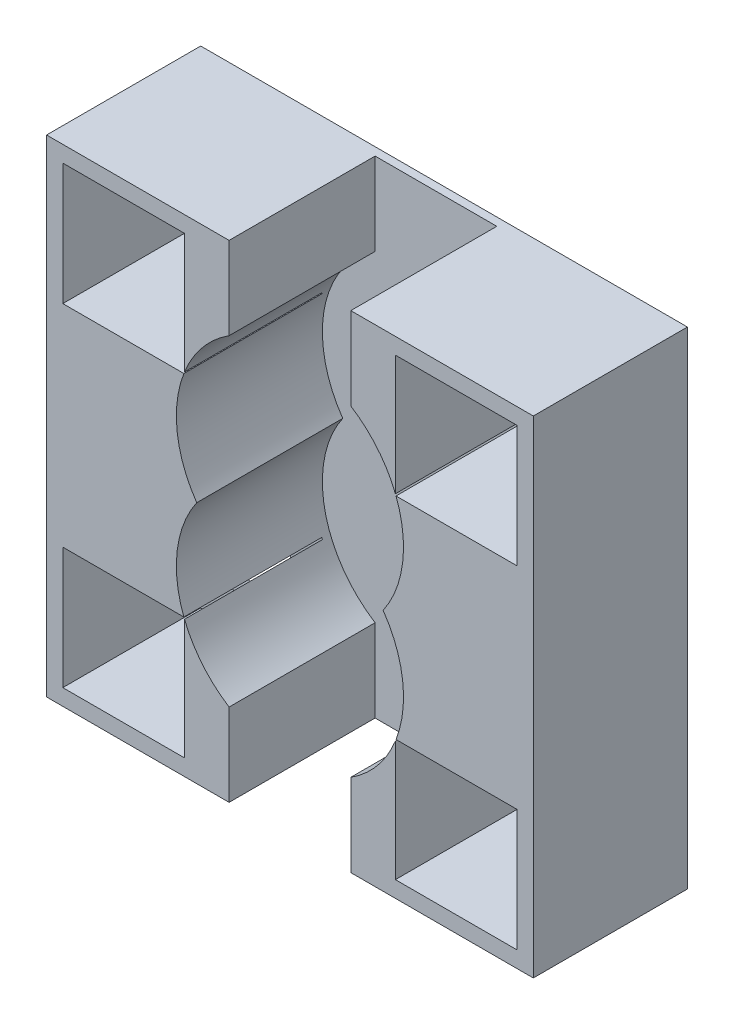
SolidWorks part; units mm, degrees
ref_plane "Plano frontal" through (0, 0, 0) normal (0, 0, 1) x (1, 0, 0)
ref_plane "Plano superior" through (0, 0, 0) normal (0, 1, 0) x (1, 0, 0)
ref_plane "Plano direito" through (0, 0, 0) normal (1, 0, 0) x (0, 0, -1)
sketch "Esboço1" plane through (0, 0, 0) normal (0, 0, 1) x (1, 0, 0)
  line L44 (-0.1299, 58.4128) -> (59.8701, 58.4128)
  line L45 (-0.1299, 58.4128) -> (-0.1299, -1.5872)
  line L46 (-0.1299, -1.5872) -> (59.8701, -1.5872)
  line L51 (59.8701, 58.4128) -> (59.8701, -1.5872)
  dimension "D1" = 60
  dimension "D2" = 60
extrude "Ressalto-extrusão2" add sketch "Esboço1" along normal blind 1 contours L45 L44 L51 L46
sketch "Esboço10" plane through (0, 0, 0) normal (0, 0, 1) x (1, 0, 0)
  line L9 (-0.1299, 58.4128) -> (59.8701, 58.4128)
  line L10 (-0.1299, 58.4128) -> (-0.1299, -1.5872)
  line L11 (-0.1299, -1.5872) -> (59.8701, -1.5872)
  line L12 (59.8701, 58.4128) -> (59.8701, -1.5872)
  arc A1 (18.381, 28.4128) -> (41.3593, 28.4128) centre (29.8701, 20.4128) ccw
  arc A2 (41.3593, 28.4128) -> (18.381, 28.4128) centre (29.8701, 36.4128) ccw
  dimension "D2" = 28
  dimension "D4" = 28
extrude "Ressalto-extrusão5" add sketch "Esboço10" along normal blind 19
sketch "Esboço13" plane through (0, 0, 19) normal (0, 0, 1) x (1, 0, 0)
  line L0 (59.8701, 58.4128) -> (-0.1299, 58.4128) construction
  line L1 (1.8701, 56.4128) -> (16.8701, 56.4128)
  line L2 (1.8701, 56.4128) -> (1.8701, 41.4128)
  line L3 (1.8701, 41.4128) -> (16.8701, 41.4128)
  line L4 (16.8701, 56.4128) -> (16.8701, 41.4128)
  line L5 (42.8701, 56.4128) -> (57.8701, 56.4128)
  line L6 (42.8701, 56.4128) -> (42.8701, 41.4128)
  line L7 (42.8701, 41.4128) -> (57.8701, 41.4128)
  line L8 (57.8701, 56.4128) -> (57.8701, 41.4128)
  line L9 (1.8701, 15.4128) -> (16.8701, 15.4128)
  line L10 (1.8701, 15.4128) -> (1.8701, 0.4128)
  line L11 (1.8701, 0.4128) -> (16.8701, 0.4128)
  line L12 (16.8701, 15.4128) -> (16.8701, 0.4128)
  line L13 (42.8701, 15.4128) -> (57.8701, 15.4128)
  line L14 (42.8701, 15.4128) -> (42.8701, 0.4128)
  line L15 (42.8701, 0.4128) -> (57.8701, 0.4128)
  line L16 (57.8701, 15.4128) -> (57.8701, 0.4128)
  line L17 (-0.1299, 58.4128) -> (-0.1299, -1.5872) construction
  line L18 (59.8701, -1.5872) -> (59.8701, 58.4128) construction
  line L19 (-0.1299, -1.5872) -> (59.8701, -1.5872) construction
  dimension "D1" = 2
  dimension "D2" = 2
  dimension "D3" = 2
  dimension "D4" = 2
  dimension "D5" = 2
  dimension "D6" = 2
  dimension "D7" = 2
  dimension "D8" = 2
  dimension "D9" = 15
  dimension "D10" = 15
  dimension "D11" = 15
  dimension "D12" = 15
  dimension "D13" = 15
  dimension "D14" = 15
  dimension "D15" = 15
  dimension "D16" = 15
extrude "Corte-extrusão7" cut sketch "Esboço13" against normal blind 17
sketch "Esboço14" plane through (0, 0, 19) normal (0, 0, 1) x (1, 0, 0)
  line L0 (16.8701, 56.4128) -> (1.8701, 56.4128) construction
  line L1 (1.8701, 56.4128) -> (1.8701, 41.4128) construction
  line L2 (16.7934, 15.4128) -> (1.8701, 15.4128) construction
  line L3 (1.8701, 15.4128) -> (1.8701, 0.4128) construction
  line L4 (42.8701, 0.4128) -> (57.8701, 0.4128) construction
  line L5 (57.8701, 0.4128) -> (57.8701, 15.4128) construction
  line L6 (42.9468, 41.4128) -> (57.8701, 41.4128) construction
  line L7 (57.8701, 41.4128) -> (57.8701, 56.4128) construction
  circle A0 centre (9.3701, 48.9128) radius 5
  circle A1 centre (9.3701, 7.9128) radius 5
  circle A2 centre (50.3701, 7.9128) radius 5
  circle A3 centre (50.3701, 48.9128) radius 5
  dimension "D1" = 10
  dimension "D2" = 7.5
  dimension "D4" = 10
  dimension "D5" = 10
  dimension "D6" = 10
  dimension "D7" = 7.5
  dimension "D8" = 7.5
  dimension "D9" = 7.5
  dimension "D10" = 7.5
  dimension "D11" = 7.5
  dimension "D12" = 7.5
  dimension "D3" = 7.5
extrude "Corte-extrusão8" cut sketch "Esboço14" against normal through all
sketch "Esboço15" plane through (0, 0, 19) normal (0, 0, 1) x (1, 0, 0)
  line L0 (-0.1299, -1.5872) -> (59.8701, -1.5872) construction
  line L2 (22.3701, 8.5912) -> (22.3701, -1.5872)
  line L3 (22.3701, -1.5872) -> (37.3701, -1.5872)
  line L4 (37.3701, 8.5912) -> (37.3701, -1.5872)
  line L5 (22.3701, 58.4128) -> (37.3701, 58.4128)
  line L6 (22.3701, 58.4128) -> (22.3701, 48.2343)
  line L8 (37.3701, 58.4128) -> (37.3701, 48.2343)
  line L9 (59.8701, -1.5872) -> (59.8701, 58.4128) construction
  line L10 (59.8701, 58.4128) -> (-0.1299, 58.4128) construction
  circle A0 centre (29.8701, 28.4128) radius 4.5
  arc A1 (22.3701, 8.5912) -> (37.3701, 8.5912) centre (29.8701, 20.4128) ccw
  arc A2 (37.3701, 48.2343) -> (22.3701, 48.2343) centre (29.8701, 36.4128) ccw
  dimension "D4" = 9
  dimension "D1" = 15
  dimension "D2" = 15
  dimension "D3" = 0
  dimension "D5" = 30
  dimension "D6" = 30
  dimension "D8" = 7.5
  dimension "D9" = 0
extrude "Corte-extrusão9" cut sketch "Esboço15" against normal blind 18
